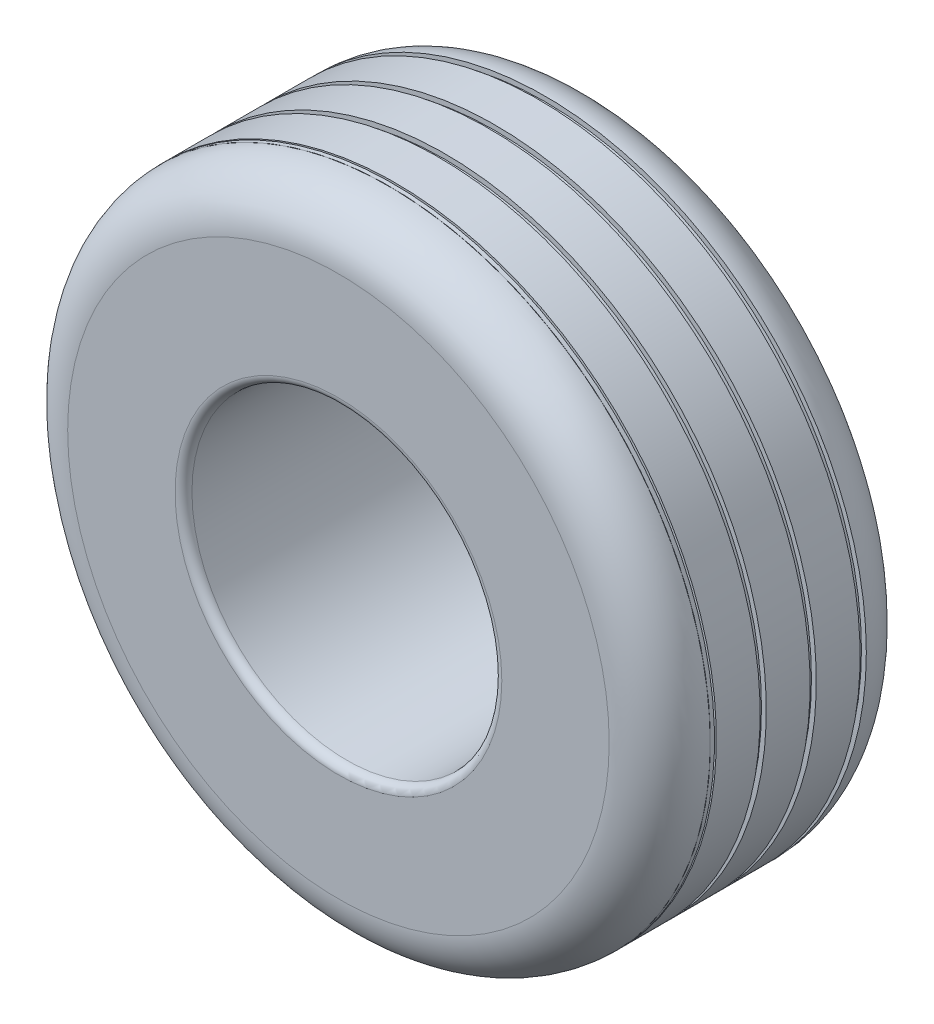
SolidWorks part; units mm, degrees
material "POLYURETHANE (11671)"
ref_plane "Front Plane" through (0, 0, 0) normal (0, 0, 1) x (1, 0, 0)
ref_plane "Top Plane" through (0, 0, 0) normal (0, 1, 0) x (1, 0, 0)
ref_plane "Right Plane" through (0, 0, 0) normal (1, 0, 0) x (0, 0, -1)
sketch "Sketch1" plane through (0, 0, 0) normal (0, 0, 1) x (1, 0, 0)
  circle A0 centre (0, 0) radius 190.5
  dimension "D1" = 381
extrude "Boss-Extrude2" add sketch "Sketch1" along normal blind 152.4
sketch "Sketch2" plane through (0, 0, 152.4) normal (0, 0, 1) x (1, 0, 0)
  circle A0 centre (0, 0) radius 91.8462
extrude "Cut-Extrude1" cut sketch "Sketch2" against normal through all
fillet "Fillet6" radius 30 1 edges at (190.5, 0, 152.4)
fillet "Fillet7" radius 5 1 edges at (91.8462, 0, 152.4)
fillet "Fillet8" radius 30 1 edges at (190.5, 0, 0)
fillet "Fillet9" radius 5 1 edges at (91.8462, 0, 0)
sketch "Sketch12" plane through (0, 0, 0) normal (1, 0, 0) x (0, 0, -1)
  line L0 (-121.1869, 0) -> (-121.1869, 188.251) construction
  line L1 (-122.4, 190.5) -> (-119.9738, 190.5)
  line L2 (-122.4, 190.5) -> (-122.4, 188.251)
  line L3 (-122.4, 188.251) -> (-119.9738, 188.251)
  line L4 (-119.9738, 190.5) -> (-119.9738, 188.251)
  line L5 (0, 0) -> (-121.1869, 0) construction
sketch "Sketch15" plane through (0, 0, 0) normal (1, 0, 0) x (0, 0, -1)
  line L0 (-122.5432, 196.8659) -> (-122.5432, 187.6142)
  line L1 (-122.5432, 187.6142) -> (-118.8792, 187.6142)
  line L2 (-118.8792, 187.6142) -> (-118.8792, 196.8659)
  line L3 (-118.8792, 196.8659) -> (-122.5432, 196.8659)
  line L4 (0, 0) -> (-371.7321, 0) construction
revolve "Cut-Revolve2" cut sketch "Sketch15" angle 360 about L4
ref_axis "Axis1" through (0, 0, 118.8792) along (0, 0, -1)
pattern_linear "LPattern1" count 4 spacing 29.63 along (0, 0, -1) of "Cut-Revolve2"
revolve "Revolve6" add sketch "Sketch12" angle 360 about L5
sketch "Sketch16" plane through (0, 0, 0) normal (0, 1, 0) x (1, 0, 0)
  line L0 (-180.7292, -9.6452) -> (-168.9263, -9.6452)
  line L1 (-94.2524, -9.6452) -> (-94.2524, -141.6271)
  line L2 (-94.2524, -141.6271) -> (-99.0771, -141.6271)
  line L3 (-180.7292, -9.6452) -> (-180.7292, -19.9637)
  line L4 (-180.7292, -129.7648) -> (-185.9701, -129.7648)
  line L5 (-185.9701, -129.7648) -> (-185.9701, -19.9637)
  line L6 (-185.9701, -19.9637) -> (-180.7292, -19.9637)
  line L7 (-180.7292, -129.7648) -> (-180.7292, -141.6271)
  line L8 (-168.9263, -141.6271) -> (-168.9263, -149.5607)
  line L9 (-168.9263, -149.5607) -> (-99.0771, -149.5607)
  line L10 (-99.0771, -149.5607) -> (-99.0771, -141.6271)
  line L11 (-94.2524, -75.6361) -> (-185.9701, -75.6361) construction
  line L12 (-99.0771, -1.7116) -> (-99.0771, -9.6452)
  line L13 (-168.9263, -1.7116) -> (-99.0771, -1.7116)
  line L14 (-168.9263, -9.6452) -> (-168.9263, -1.7116)
  line L15 (-168.9263, -141.6271) -> (-180.7292, -141.6271)
  line L16 (-99.0771, -9.6452) -> (-94.2524, -9.6452)
revolve "Cut-Revolve3" cut sketch "Sketch16" angle 360 about axis through (0, 0, 118.8792) along (0, 0, -1)
